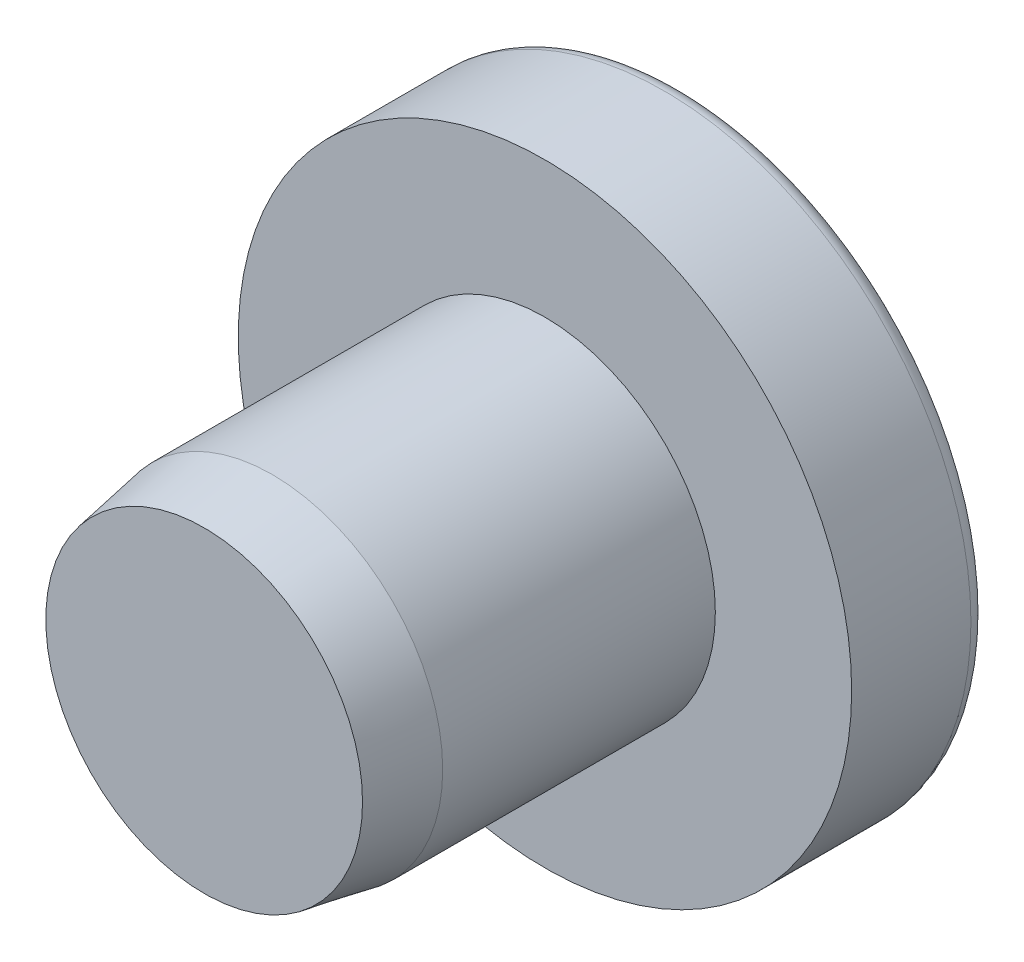
SolidWorks part; units mm, degrees
ref_plane "前视基准面" through (0, 0, 0) normal (0, 0, 1) x (1, 0, 0)
ref_plane "上视基准面" through (0, 0, 0) normal (0, 1, 0) x (1, 0, 0)
ref_plane "右视基准面" through (0, 0, 0) normal (1, 0, 0) x (0, 0, -1)
sketch "草图1" plane through (0, 0, 0) normal (0, 0, 1) x (1, 0, 0)
  circle A0 centre (0, 0) radius 9
  dimension "D1" = 18
extrude "凸台-拉伸1" add sketch "草图1" along normal blind 4
sketch "草图2" plane through (0, 0, 4) normal (0, 0, 1) x (1, 0, 0)
  circle A0 centre (0, 0) radius 5
  dimension "D1" = 10
extrude "凸台-拉伸2" add sketch "草图2" along normal blind 10
fillet "圆角1" radius 0.5 1 edges at (9, 0, 0)
chamfer "倒角1" distance 2 angle 10 1 edges at (5, 0, 14)
